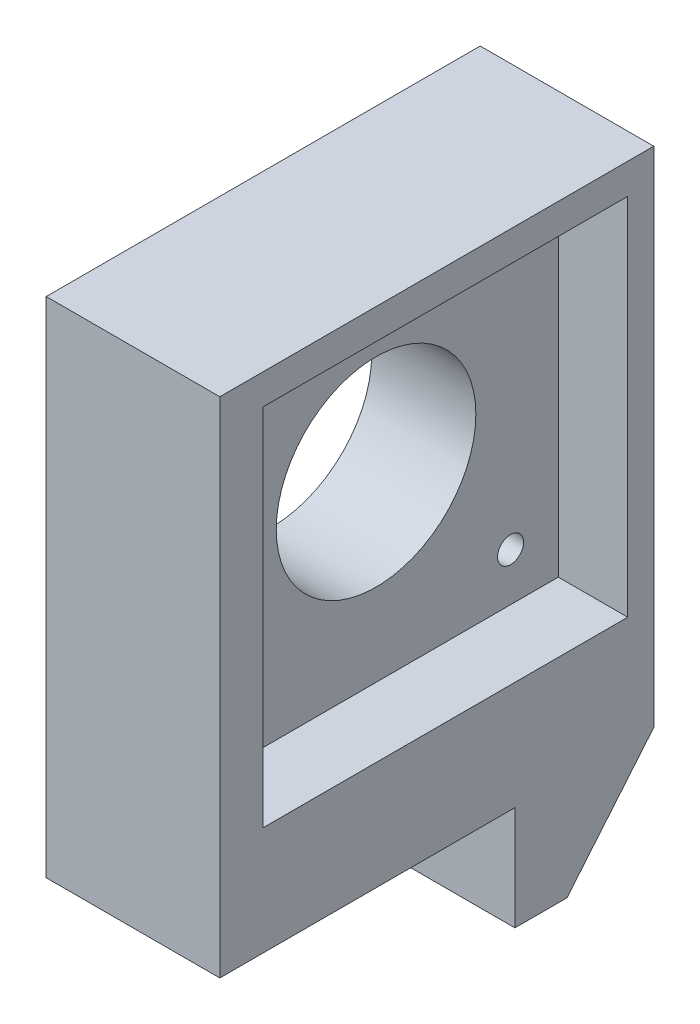
SolidWorks part; units mm, degrees
ref_plane "Front Plane" through (0, 0, 0) normal (0, 0, 1) x (1, 0, 0)
ref_plane "Top Plane" through (0, 0, 0) normal (0, 1, 0) x (1, 0, 0)
ref_plane "Right Plane" through (0, 0, 0) normal (1, 0, 0) x (0, 0, -1)
sketch "Sketch1" plane through (0, 0, 0) normal (0, 1, 0) x (1, 0, 0)
  line L1 (0, 0) -> (-20, 0)
  line L2 (0, 0) -> (0, -50)
  line L3 (0, -50) -> (-20, -50)
  line L4 (-20, 0) -> (-20, -50)
  dimension "D1" = 20
  dimension "D2" = 50
extrude "Boss-Extrude1" add sketch "Sketch1" along normal blind 70
sketch "Sketch2" plane through (0, 0, 0) normal (1, 0, 0) x (0, 0, -1)
  line L0 (-50, 70) -> (0, 70) construction
  line L1 (0, 70) -> (0, 0) construction
  line L2 (0, 45.5) -> (-50, 45.5) construction
  line L3 (-24, 70) -> (-24, 0) construction
  line L4 (-24, 70) -> (-24, 0) construction
  line L5 (-50, 0) -> (0, 0) construction
  line L7 (-50, 70) -> (-50, 0) construction
  circle A0 centre (-8.5, 61) radius 1.5
  circle A4 centre (-24, 45.5) radius 11.5
  circle A5 centre (-8.5, 30) radius 1.5
  circle A8 centre (-39.5, 30) radius 1.5
  circle A9 centre (-39.5, 61) radius 1.5
  point P24 (-25, 0)
  dimension "D1" = 3
  dimension "D2" = 9
  dimension "D3" = 15.5
  dimension "D6" = 23
  dimension "D7" = 0
  dimension "D8" = 0
  dimension "D4" = 15.5
  dimension "D9" = 1
  dimension "D5" = 0
extrude "Cut-Extrude2" cut sketch "Sketch2" against normal blind 60
sketch "Sketch4" plane through (0, 0, 0) normal (1, 0, 0) x (0, 0, -1)
  line L0 (0, 70) -> (0, 0) construction
  line L1 (-50, 0) -> (-16, 0)
  line L2 (-50, 0) -> (-50, 12)
  line L3 (-50, 12) -> (-16, 12)
  line L4 (-16, 0) -> (-16, 12)
  dimension "D1" = 12
  dimension "D2" = 16
extrude "Cut-Extrude3" cut sketch "Sketch4" against normal blind 60
sketch "Sketch8" plane through (0, 0, 0) normal (0, 0, -1) x (-1, 0, 0)
  line L0 (0, 0) -> (20, 0) construction
  line L1 (20, 70) -> (20, 0) construction
  line L2 (0, 70) -> (0, 0) construction
  circle A0 centre (15, 6) radius 2
  circle A1 centre (5, 6) radius 2
  dimension "D1" = 4
  dimension "D2" = 6
  dimension "D3" = 5
  dimension "D4" = 4
  dimension "D5" = 0
  dimension "D6" = 5
extrude "Cut-Extrude5" cut sketch "Sketch8" against normal blind 15
sketch "Sketch9" plane through (0, 0, 0) normal (1, 0, 0) x (0, 0, -1)
  line L0 (0, 49.6538) -> (-50, 41) construction
  line L1 (-3, 66.5) -> (-45, 66.5)
  line L2 (-3, 66.5) -> (-3, 24.5)
  line L3 (-3, 24.5) -> (-45, 24.5)
  line L4 (-45, 66.5) -> (-45, 24.5)
  line L5 (0, 70) -> (0, 0) construction
  line L6 (-50, 70) -> (-50, 12) construction
  line L7 (-24, 70) -> (-24, 12) construction
  line L8 (-50, 70) -> (0, 70) construction
  line L9 (-16, 12) -> (-50, 12) construction
  circle A0 centre (-24, 45.5) radius 11.5 construction
  dimension "D1" = 0
  dimension "D2" = 42
  dimension "D3" = 21
  dimension "D4" = 42
  dimension "D5" = 21
  dimension "D6" = 0
extrude "Cut-Extrude6" cut sketch "Sketch9" against normal blind 8
sketch "Sketch11" plane through (0, 0, 0) normal (1, 0, 0) x (0, 0, -1)
  line L7 (-10, 0) -> (0, 0)
  line L8 (-16, 0) -> (0, 0) construction
  line L9 (0, 0) -> (0, 12)
  line L10 (0, 70) -> (0, 0) construction
  line L11 (0, 12) -> (-10, 0)
  line L12 (-16, 12) -> (-50, 12) construction
  dimension "D1" = 0
  dimension "D2" = 6
extrude "Cut-Extrude8" cut sketch "Sketch11" against normal blind 30
sketch "Sketch17" plane through (0, 0, 0) normal (0, 0, -1) x (-1, 0, 0)
  circle A0 centre (15, 6) radius 3.5
  circle A1 centre (5, 6) radius 3.5
  dimension "D1" = 7
  dimension "D2" = 7
extrude "Cut-Extrude13" cut sketch "Sketch17" against normal blind 9.1811
sketch "Sketch18" plane through (-20, 0, 0) normal (-1, 0, 0) x (0, 0, 1)
  line L0 (50, 70) -> (50, 12) construction
  circle A0 centre (46, 20) radius 1.5
  circle A1 centre (39.5, 30) radius 1.5 construction
  circle A2 centre (39, 20) radius 1.5
  dimension "D1" = 3
  dimension "D2" = 10
  dimension "D3" = 4
  dimension "D4" = 3
  dimension "D5" = 0
  dimension "D6" = 7
extrude "Cut-Extrude14" cut sketch "Sketch18" against normal blind 7
